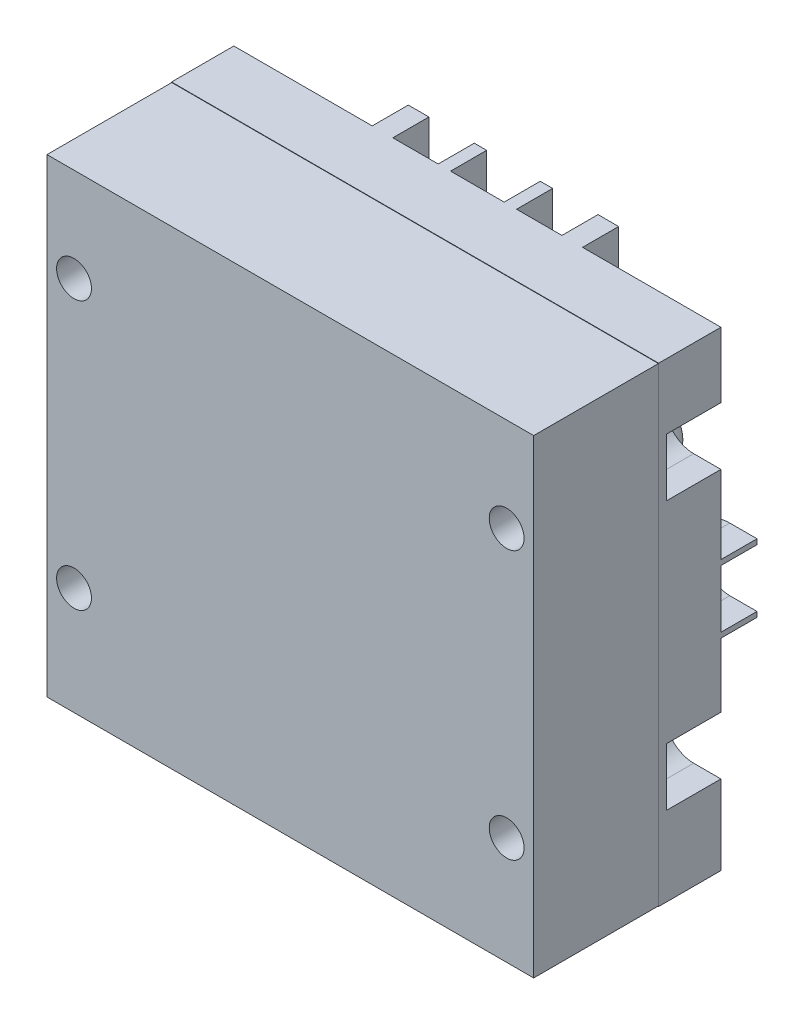
SolidWorks part; units mm, degrees
ref_plane "Front Plane" through (0, 0, 0) normal (0, 0, 1) x (1, 0, 0)
ref_plane "Top Plane" through (0, 0, 0) normal (0, 1, 0) x (1, 0, 0)
ref_plane "Right Plane" through (0, 0, 0) normal (1, 0, 0) x (0, 0, -1)
sketch "Sketch1" plane through (0, 0, 0) normal (0, 0, 1) x (1, 0, 0)
  line L1 (-29.9974, -28.9814) -> (29.9974, -28.9814)
  line L2 (-29.9974, -28.9814) -> (-29.9974, 28.9814)
  line L3 (-29.9974, 28.9814) -> (29.9974, 28.9814)
  line L4 (29.9974, -28.9814) -> (29.9974, 28.9814)
  line L5 (-29.9974, -28.9814) -> (29.9974, 28.9814) construction
  line L6 (-29.9974, 28.9814) -> (29.9974, -28.9814) construction
  point P0 (0, 0)
  dimension "D1" = 57.9628
  dimension "D2" = 59.9948
extrude "Boss-Extrude1" add sketch "Sketch1" along normal blind 27.4828
sketch "Sketch2" plane through (0, 0, 27.4828) normal (0, 0, 1) x (1, 0, 0)
  line L0 (-29.9974, -28.9814) -> (29.9974, -28.9814) construction
  line L1 (-29.9974, 28.9814) -> (-29.9974, -28.9814) construction
  circle A0 centre (-26.6446, -15.6464) radius 2.1463
  circle A1 centre (-26.6446, 17.3736) radius 2.1463
  dimension "D1" = 4.2926
  dimension "D2" = 13.335
  dimension "D3" = 3.3528
  dimension "D4" = 33.02
extrude "Cut-Extrude1" cut sketch "Sketch2" against normal through all
mirror "Mirror1" about plane through (0, 0, 0) normal (1, 0, 0) of "Cut-Extrude1"
sketch "Sketch3" plane through (0, 0, 0) normal (0, 0, -1) x (-1, 0, 0)
  line L0 (-26.6446, 20.9296) -> (-29.9974, 20.9296)
  line L1 (-29.9974, -28.9814) -> (-29.9974, 28.9814) construction
  line L2 (-29.9974, 20.9296) -> (-29.9974, 13.8176)
  line L3 (-29.9974, 13.8176) -> (-26.6446, 13.8176)
  line L5 (-26.6446, -12.0904) -> (-29.9974, -12.0904)
  line L6 (-29.9974, -12.0904) -> (-29.9974, -19.2024)
  line L7 (-29.9974, -19.2024) -> (-26.6446, -19.2024)
  line L8 (26.6446, 20.9296) -> (29.9974, 20.9296)
  line L9 (29.9974, 28.9814) -> (29.9974, -28.9814) construction
  line L10 (29.9974, 20.9296) -> (29.9974, 13.8176)
  line L11 (29.9974, 13.8176) -> (26.6446, 13.8176)
  line L13 (26.6446, -12.0904) -> (29.9974, -12.0904)
  line L14 (29.9974, -12.0904) -> (29.9974, -19.2024)
  line L15 (29.9974, -19.2024) -> (26.6446, -19.2024)
  arc A0 (26.6446, 20.9296) -> (26.6446, 13.8176) centre (26.6446, 17.3736) ccw
  arc A1 (26.6446, -12.0904) -> (26.6446, -19.2024) centre (26.6446, -15.6464) ccw
  arc A3 (-26.6446, -19.2024) -> (-26.6446, -12.0904) centre (-26.6446, -15.6464) ccw
  arc A4 (-26.6446, 13.8176) -> (-26.6446, 20.9296) centre (-26.6446, 17.3736) ccw
  dimension "D1" = 7.112
extrude "Cut-Extrude2" cut sketch "Sketch3" against normal blind 11.176
sketch "Sketch4" plane through (0, 0, 0) normal (0, 0, -1) x (-1, 0, 0)
  line L0 (26.6446, 17.3736) -> (26.6446, 0) construction
  line L1 (26.6446, 4.196) -> (29.9974, 4.196)
  line L2 (29.9974, 13.8176) -> (29.9974, -12.0904) construction
  line L3 (29.9974, 4.196) -> (29.9974, 3.556)
  line L4 (29.9974, -4.196) -> (26.6446, -4.196)
  line L5 (26.6446, 3.556) -> (29.9974, 3.556)
  line L6 (26.6446, -3.556) -> (29.9974, -3.556)
  line L7 (29.9974, -3.556) -> (29.9974, -4.196)
  line L8 (22.4486, 0) -> (4.064, 0) construction
  line L9 (4.064, 0) -> (4.064, 28.9814) construction
  line L10 (-29.9974, 28.9814) -> (29.9974, 28.9814) construction
  line L11 (11.684, -28.9814) -> (11.684, 28.9814) construction
  line L12 (29.9974, -28.9814) -> (-29.9974, -28.9814) construction
  line L13 (12.954, -28.9814) -> (12.954, -0.762)
  line L14 (10.414, -28.9814) -> (10.414, -0.762)
  line L15 (22.5184, 0.762) -> (12.954, 0.762)
  line L16 (4.826, 0.762) -> (4.826, 28.9814)
  line L17 (22.5184, -0.762) -> (12.954, -0.762)
  line L18 (3.302, -0.762) -> (3.302, 28.9814)
  line L19 (10.414, 0.762) -> (4.826, 0.762)
  line L20 (10.414, -0.762) -> (3.302, -0.762)
  line L21 (22.4486, 0.762) -> (4.826, 0.762) construction
  line L22 (10.414, 0.762) -> (10.414, 28.9814)
  line L23 (22.4486, -0.762) -> (3.302, -0.762) construction
  line L24 (12.954, 0.762) -> (12.954, 28.9814)
  line L25 (10.414, -28.9814) -> (10.414, 28.9814) construction
  line L26 (4.826, 28.9814) -> (10.414, 28.9814)
  line L27 (12.954, -28.9814) -> (12.954, 28.9814) construction
  line L28 (12.954, 28.9814) -> (29.9974, 28.9814)
  line L29 (29.9974, 28.9814) -> (29.9974, 4.196)
  line L30 (29.9974, 3.556) -> (29.9974, -3.556)
  line L31 (29.9974, -3.556) -> (29.9538, -3.4833)
  line L32 (29.9974, -4.196) -> (29.9974, -28.9814)
  line L33 (29.9974, -28.9814) -> (12.954, -28.9814)
  line L34 (10.414, -28.9814) -> (0, -28.9814)
  line L35 (0, -28.9814) -> (0, 28.9814)
  line L36 (0, 28.9814) -> (3.302, 28.9814)
  arc A0 (26.6446, 3.556) -> (26.6446, -3.556) centre (26.6446, 0) ccw
  arc A1 (26.6446, 4.196) -> (22.5184, 0.762) centre (26.6446, 0) ccw
  arc A2 (22.5184, -0.762) -> (26.6446, -4.196) centre (26.6446, 0) ccw
  dimension "D1" = 7.112
  dimension "D2" = 0.64
  dimension "D3" = 4.064
  dimension "D4" = 7.62
  dimension "D5" = 1.27
  dimension "D6" = 1.27
  dimension "D7" = 0.762
  dimension "D8" = 0.762
extrude "Cut-Extrude3" cut sketch "Sketch4" against normal blind 4.445
mirror "Mirror2" about plane through (0, 0, 0) normal (1, 0, 0) of "Cut-Extrude3"
sketch "Sketch5" plane through (0, 0, 27.4828) normal (0, 0, 1) x (1, 0, 0)
  line L0 (29.9974, 28.9814) -> (-29.9974, 28.9814) construction
  line L1 (-29.972, -28.9306) -> (29.972, -28.9306)
  line L2 (-29.972, -28.9306) -> (-29.972, 28.9306)
  line L3 (-29.972, 28.9306) -> (29.972, 28.9306)
  line L4 (29.972, -28.9306) -> (29.972, 28.9306)
  line L5 (-29.972, -28.9306) -> (29.972, 28.9306) construction
  line L6 (-29.972, 28.9306) -> (29.972, -28.9306) construction
  line L7 (29.9974, -28.9814) -> (29.9974, 28.9814) construction
  line L8 (-29.9974, -28.9814) -> (29.9974, -28.9814) construction
  line L9 (-29.9974, 28.9814) -> (29.9974, 28.9814)
  line L10 (-29.9974, 28.9814) -> (-29.9974, -28.9814)
  line L11 (-29.9974, -28.9814) -> (29.9974, -28.9814)
  line L12 (29.9974, 28.9814) -> (29.9974, -28.9814)
  line L13 (-29.9974, 28.9814) -> (29.9974, -28.9814) construction
  line L14 (-29.9974, -28.9814) -> (29.9974, 28.9814) construction
  point P0 (0, 0)
  point P10 (0, 0)
  dimension "D1" = 0.0508
  dimension "D2" = 0.0254
extrude "Cut-Extrude4" cut sketch "Sketch5" against normal blind 15.367
sketch "Sketch6" plane through (0, 0, 4.445) normal (0, 0, -1) x (-1, 0, 0)
  line L1 (-17.78, 10.16) -> (17.78, 10.16) construction
  line L2 (-17.78, 10.16) -> (-17.78, -10.16) construction
  line L3 (-17.78, -10.16) -> (17.78, -10.16) construction
  line L4 (17.78, 10.16) -> (17.78, -10.16) construction
  line L5 (-17.78, 10.16) -> (17.78, -10.16) construction
  line L6 (-17.78, -10.16) -> (17.78, 10.16) construction
  circle A0 centre (-17.78, 10.16) radius 3.81
  circle A1 centre (17.78, 10.16) radius 3.81
  circle A2 centre (17.78, -10.16) radius 3.81
  circle A3 centre (-17.78, -10.16) radius 3.81
  point P0 (0, 0)
  dimension "D3" = 7.62
  dimension "D1" = 35.56
  dimension "D2" = 20.32
extrude "Boss-Extrude2" add sketch "Sketch6" along normal blind 5.207
fillet "Fillet1" radius 2.54 4 edges at (-21.59, -10.16, -0.762) (-21.59, 10.16, -0.762) (13.97, 10.16, -0.762) (13.97, -10.16, -0.762)
